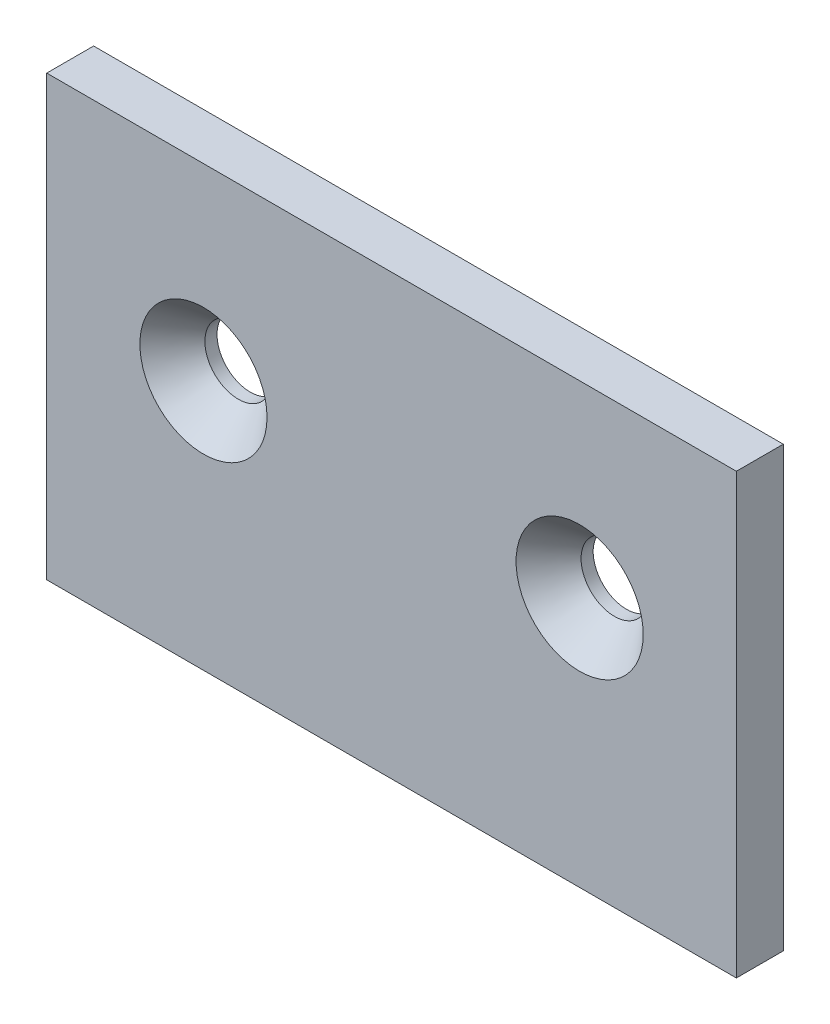
SolidWorks part; units mm, degrees
ref_plane "Front Plane" through (0, 0, 0) normal (0, 0, 1) x (1, 0, 0)
ref_plane "Top Plane" through (0, 0, 0) normal (0, 1, 0) x (1, 0, 0)
ref_plane "Right Plane" through (0, 0, 0) normal (1, 0, 0) x (0, 0, -1)
sketch "Sketch1" plane through (0, 0, 0) normal (0, 0, 1) x (1, 0, 0)
  line L1 (-34.925, -22.225) -> (34.925, -22.225)
  line L2 (-34.925, -22.225) -> (-34.925, 22.225)
  line L3 (-34.925, 22.225) -> (34.925, 22.225)
  line L4 (34.925, -22.225) -> (34.925, 22.225)
  line L5 (-34.925, -22.225) -> (34.925, 22.225) construction
  line L6 (-34.925, 22.225) -> (34.925, -22.225) construction
  point P1 (0, 0)
  dimension "D1" = 69.85
  dimension "D2" = 44.45
extrude "Boss-Extrude1" add sketch "Sketch1" along normal mid plane 4.75
hole_wizard "CSK for 1/4 Flat Head Machine Screw1" positions "Sketch3" profile "Sketch4" countersink size "1/4" standard "ANSI Inch" end condition through all
sketch "Sketch3" plane through (0, 0, 2.375) normal (0, 0, 1) x (1, 0, 0)
  line L0 (-34.925, -22.225) -> (34.925, -22.225) construction
  point P0 (-19.05, 3.175)
  dimension "D1" = 19.05
  dimension "D2" = 25.4
sketch "Sketch4" plane through (-19.05, 3.175, 2.375) normal (1, 0, 0) x (0, -1, 0)
  line L0 (0, 0) -> (0, 4.75)
  line L1 (0, 4.75) -> (3.3782, 4.75)
  line L2 (3.3782, 4.75) -> (3.3782, 3.5209)
  line L3 (3.3782, 3.5209) -> (6.4389, 0)
  line L5 (6.4389, 0) -> (0, 0)
  line L6 (-3.3782, 3.5209) -> (-6.4389, 0) construction
  line L11 (0, -6.35) -> (0, 107.95) construction
  dimension "Thru Hole Dia." = 6.7564
  dimension "Thru Hole Depth" = 4.75
  dimension "Near C'Sink Dia." = 12.8778
  dimension "Near C'Sink Angle" = 82
mirror "Mirror1" about plane through (0, 0, 0) normal (1, 0, 0) of "CSK for 1/4 Flat Head Machine Screw1"
